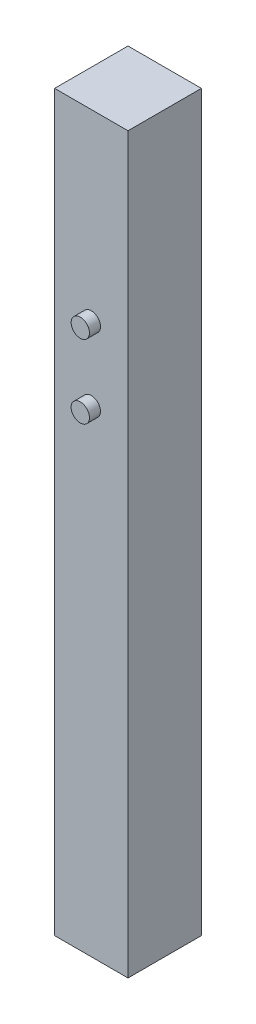
SolidWorks part; units mm, degrees
ref_plane "Front Plane" through (0, 0, 0) normal (0, 0, 1) x (1, 0, 0)
ref_plane "Top Plane" through (0, 0, 0) normal (0, 1, 0) x (1, 0, 0)
ref_plane "Right Plane" through (0, 0, 0) normal (1, 0, 0) x (0, 0, -1)
sketch "Sketch4" plane through (0, 0, 0) normal (0, 1, 0) x (1, 0, 0)
  line L0 (0, 0) -> (20, 0)
  line L1 (20, 0) -> (20, -20)
  line L2 (20, -20) -> (0, -20)
  line L3 (0, -20) -> (0, 0)
  dimension "D1" = 20
  dimension "D2" = 20
extrude "Boss-Extrude2" add sketch "Sketch4" along normal blind 200
sketch "Sketch5" plane through (0, 0, 20) normal (0, 0, 1) x (1, 0, 0)
  line L0 (10, 200) -> (10, 0) construction
  line L1 (0, 200) -> (20, 200) construction
  line L2 (0, 0) -> (20, 0) construction
  circle A0 centre (10, 150) radius 2.5
  circle A1 centre (10, 130) radius 2.5
  dimension "D1" = 5
  dimension "D2" = 5
  dimension "D3" = 20
  dimension "D4" = 50
extrude "Boss-Extrude3" add sketch "Sketch5" along normal blind 3
